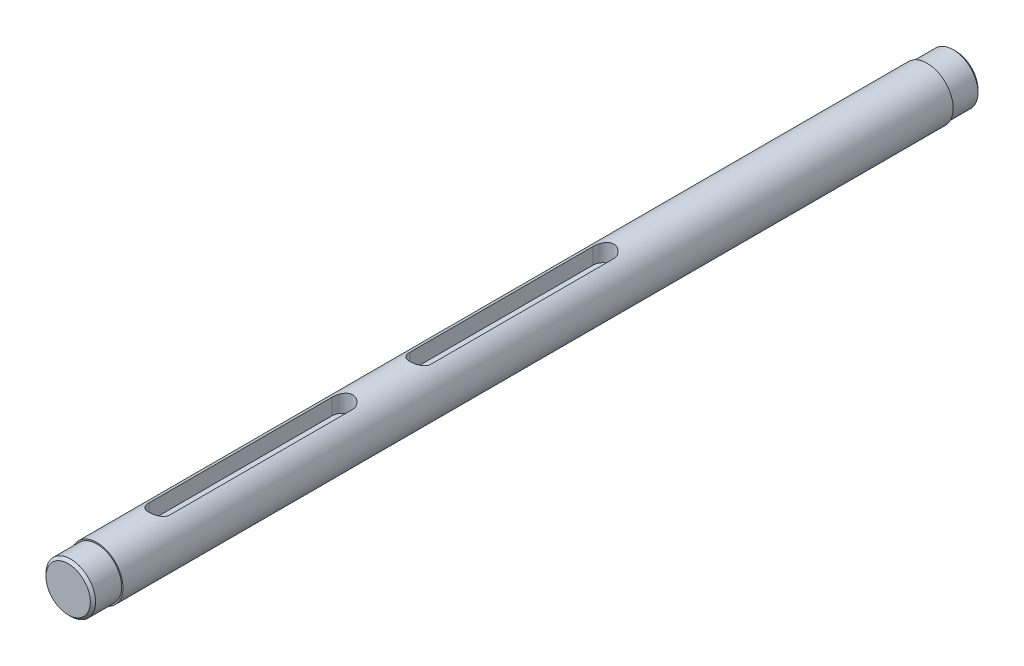
SolidWorks part; units mm, degrees
ref_plane "Alzado" through (0, 0, 0) normal (0, 0, 1) x (1, 0, 0)
ref_plane "Planta" through (0, 0, 0) normal (0, 1, 0) x (1, 0, 0)
ref_plane "Vista lateral" through (0, 0, 0) normal (1, 0, 0) x (0, 0, -1)
sketch "Croquis1" plane through (0, 0, 0) normal (0, 0, 1) x (1, 0, 0)
  circle A0 centre (0, 0) radius 5
  dimension "D1" = 10
extrude "Saliente-Extruir1" add sketch "Croquis1" along normal blind 170
sketch "Croquis2" plane through (0, 0, 170) normal (0, 0, 1) x (1, 0, 0)
  circle A0 centre (0, 0) radius 5 construction
  circle A1 centre (0, 0) radius 5
  circle A2 centre (0, 0) radius 4.75
  dimension "D1" = 0.25
extrude "Cortar-Extruir1" cut sketch "Croquis2" against normal blind 5.5
sketch "Croquis3" plane through (0, 0, 0) normal (0, 0, -1) x (-1, 0, 0)
  circle A0 centre (0, 0) radius 5 construction
  circle A1 centre (0, 0) radius 5
  circle A2 centre (0, 0) radius 4.75
  dimension "D1" = 0.25
extrude "Cortar-Extruir2" cut sketch "Croquis3" against normal blind 5.5
chamfer "Chaflán1" distance 0.5 angle 45 2 edges at (4.75, 0, 170) (-4.75, 0, 0)
ref_plane "Plano1" through (0, 5, 0) normal (0, -1, 0) x (-1, 0, 0)
sketch "Croquis4" plane through (0, 5, 0) normal (0, -1, 0) x (-1, 0, 0)
  line L0 (0, -117.5) -> (0, -152.5) construction
  line L1 (2, -117.5) -> (2, -152.5)
  line L2 (-2, -117.5) -> (-2, -152.5)
  line L4 (-4.25, -170) -> (4.25, -170) construction
  line L5 (0, -102.5) -> (0, -67.5) construction
  line L6 (-2, -102.5) -> (-2, -67.5)
  line L7 (2, -102.5) -> (2, -67.5)
  arc A0 (2, -117.5) -> (-2, -117.5) centre (0, -117.5) ccw
  arc A1 (-2, -152.5) -> (2, -152.5) centre (0, -152.5) ccw
  arc A2 (-2, -102.5) -> (2, -102.5) centre (0, -102.5) ccw
  arc A3 (2, -67.5) -> (-2, -67.5) centre (0, -67.5) ccw
  point P3 (0, -135)
  point P12 (0, -85)
  dimension "D3" = 2
  dimension "D4" = 2
  dimension "D1" = 35
  dimension "D2" = 17.5
  dimension "D5" = 35
  dimension "D6" = 67.5
extrude "Cortar-Extruir4" cut sketch "Croquis4" along normal blind 3.5
